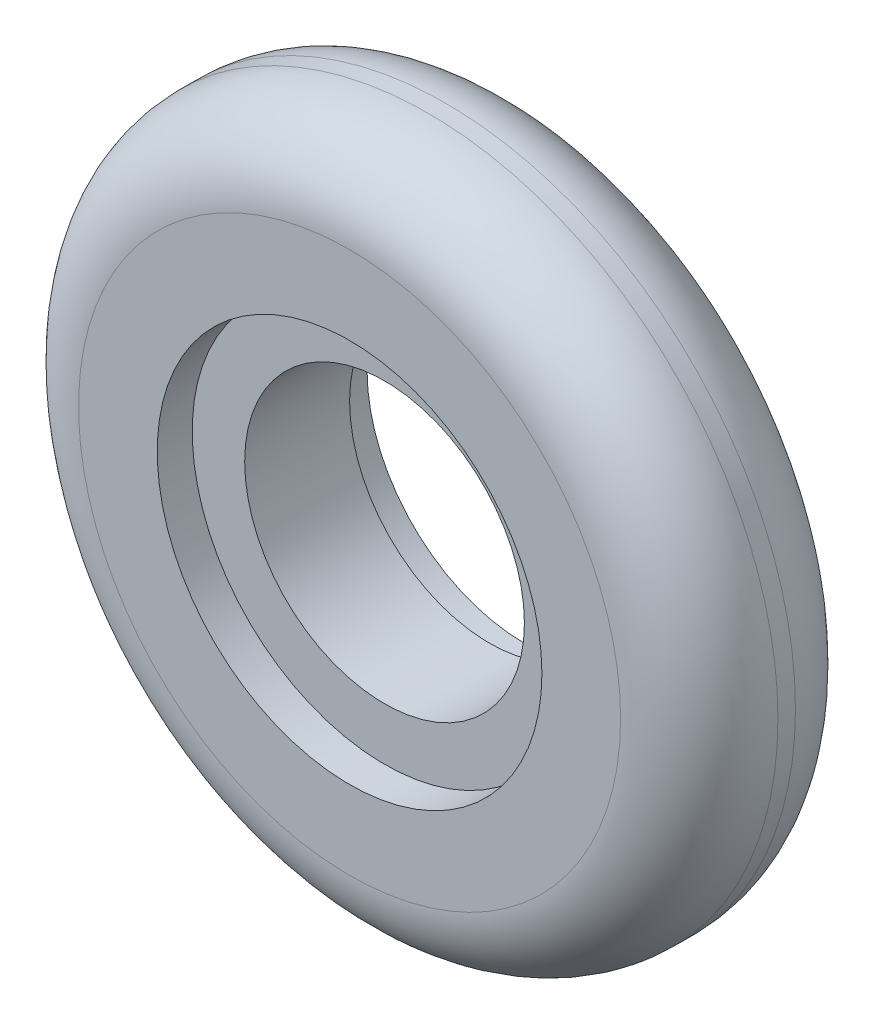
SolidWorks part; units mm, degrees
ref_plane "Front Plane" through (0, 0, 0) normal (0, 0, 1) x (1, 0, 0)
ref_plane "Top Plane" through (0, 0, 0) normal (0, 1, 0) x (1, 0, 0)
ref_plane "Right Plane" through (0, 0, 0) normal (1, 0, 0) x (0, 0, -1)
sketch "Sketch1" plane through (0, 0, 0) normal (0, 0, 1) x (1, 0, 0)
  circle A0 centre (0, 0) radius 8
  circle A1 centre (0, 0) radius 20
  dimension "D1" = 16
  dimension "D2" = 40
extrude "Boss-Extrude1" add sketch "Sketch1" along normal blind 10
fillet "Fillet1" radius 4.5 2 edges at (20, 0, 0) (20, 0, 10)
sketch "Sketch2" plane through (0, 0, 0) normal (0, 0, -1) x (-1, 0, 0)
  circle A0 centre (0, 0) radius 9
  circle A1 centre (0, 0) radius 8 construction
  dimension "D1" = 1
sketch "Sketch3" plane through (0, 0, 0) normal (0, 0, 1) x (1, 0, 0)
  circle A0 centre (0, 0) radius 5
sketch "Sketch5" plane through (0, 0, 10) normal (0, 0, 1) x (1, 0, 0)
  circle A0 centre (0, 0) radius 11
  circle A1 centre (0, 0) radius 8 construction
  dimension "D1" = 3
extrude "Cut-Extrude1" cut sketch "Sketch2" against normal blind 2
extrude "Cut-Extrude2" cut sketch "Sketch5" against normal blind 2
